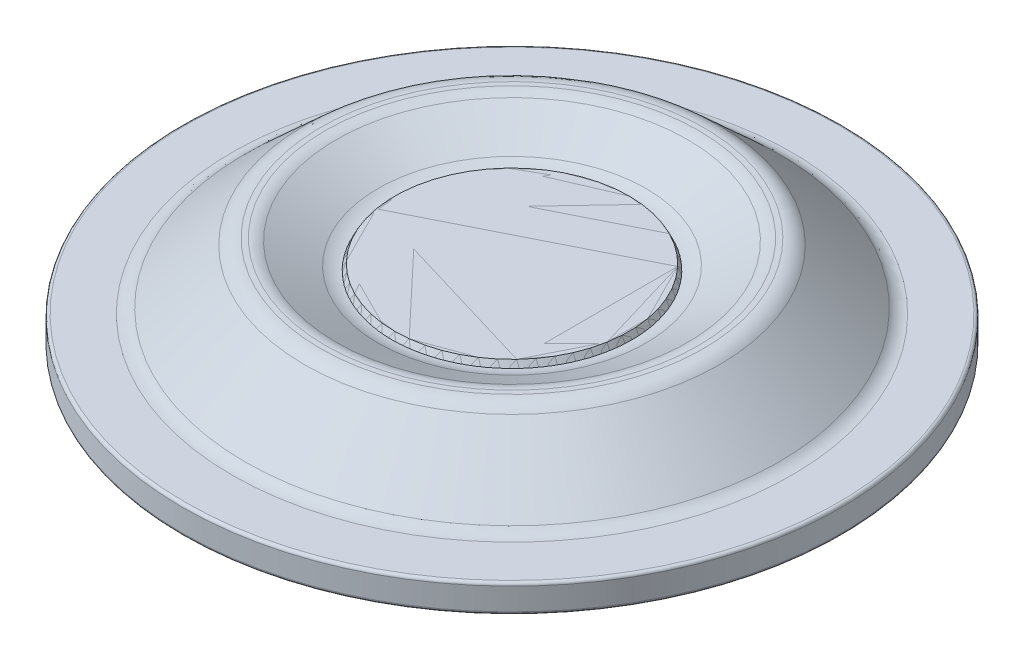
SolidWorks part; units mm, degrees
material "Nitrile Rubber"
ref_plane "Front Plane" through (0, 0, 0) normal (0, 0, 1) x (1, 0, 0)
ref_plane "Top Plane" through (0, 0, 0) normal (0, 1, 0) x (1, 0, 0)
ref_plane "Right Plane" through (0, 0, 0) normal (1, 0, 0) x (0, 0, -1)
sketch "Sketch2" plane through (0, 0, 0) normal (0, 0, 1) x (1, 0, 0)
  line L0 (29.9837, -0.4439) -> (22.8707, -4.107)
  line L1 (32.695, 0) -> (31.815, 0)
  line L2 (45.5394, -10.3406) -> (35.3967, -1.0503)
  line L3 (20.5, -4.8) -> (20, -3.8)
  line L4 (47.75, -11.2) -> (55.75, -11.2)
  line L5 (20, -3.8) -> (0, -3.8)
  line L6 (56.25, -11.7) -> (56.25, -15.5)
  line L7 (0, -9.3) -> (15, -9.3)
  line L8 (51.5, -15.25) -> (51.5, -13.3)
  line L9 (51, -12.8) -> (47.75, -12.8)
  line L11 (17.8335, -8.6132) -> (29.9624, -2.367)
  line L12 (0, -3.8) -> (0, -9.3)
  line L14 (44.2015, -11.4205) -> (35.0622, -3.0493)
  line L18 (0, 0) -> (0, -20.9104) construction
  line L20 (55.75, -16) -> (52.25, -16)
  arc A0 (20.5, -4.8) -> (22.8707, -4.107) centre (19.8947, 1.6718) ccw
  arc A1 (29.9624, -2.367) -> (35.0622, -3.0493) centre (32.0227, -6.3676) cw
  arc A2 (35.3967, -1.0503) -> (32.695, 0) centre (32.695, -4) ccw
  arc A3 (31.815, 0) -> (29.9837, -0.4439) centre (31.815, -4) ccw
  arc A4 (45.5394, -10.3406) -> (47.75, -11.2) centre (47.75, -7.9272) ccw
  arc A5 (44.2015, -11.4205) -> (47.75, -12.8) centre (47.75, -7.5463) ccw
  arc A6 (56.25, -15.5) -> (55.75, -16) centre (55.75, -15.5) cw
  arc A7 (51.5, -15.25) -> (52.25, -16) centre (52.25, -15.25) ccw
  arc A8 (55.75, -11.2) -> (56.25, -11.7) centre (55.75, -11.7) cw
  arc A9 (51.5, -13.3) -> (51, -12.8) centre (51, -13.3) ccw
  arc A10 (15, -9.3) -> (17.8335, -8.6132) centre (15, -3.1111) ccw
  point P21 (32.75, -0.9314)
  point P28 (34.25, 0)
  point P37 (16.5, -9.3)
  dimension "D9" = 68.5
  dimension "D13" = 3.8
  dimension "D14" = 4.8
  dimension "D16" = 65.5
  dimension "D19" = 0.5
  dimension "D21" = 30
  dimension "D5" = 0.5
  dimension "D18" = 5.5
  dimension "D7" = 0.5
  dimension "D24" = 6.5
  dimension "D25" = 0.75
  dimension "D27" = 1
  dimension "D12" = 40
  dimension "D23" = 5.2537
  dimension "D26" = 1.7
  dimension "D15" = 95.5
  dimension "D10" = 4.5
  dimension "D20" = 4
  dimension "D3" = 112.5
  dimension "D4" = 103
  dimension "D6" = 1.6
  dimension "D8" = 16
  dimension "D11" = 41
  dimension "D17" = 33
  dimension "D22" = 1.7
revolve "Revolve1" add sketch "Sketch2" angle 360 about L18
sketch "Sketch3" plane through (0, 0, 0) normal (0, 0, 1) x (1, 0, 0)
  line L0 (0, -20.9104) -> (0, 11.3964) construction
  line L1 (20.5, -4.8) -> (14.0845, -5.4)
  line L2 (14.0845, -5.4) -> (0, -5.4)
  line L5 (20, -3.8) -> (0, -3.8) construction
  line L6 (20.5, -4.8) -> (20, -3.8) construction
  line L7 (20.5, -4.8) -> (20, -3.8)
  line L8 (20, -3.8) -> (0, -3.8)
  line L9 (0, -5.4) -> (0, -3.8)
  arc A0 (20.5, -4.8) -> (22.8707, -4.107) centre (19.8947, 1.6718) ccw construction
  dimension "D1" = 1.6
revolve "Revolve2" add sketch "Sketch3" angle 360 about L0
